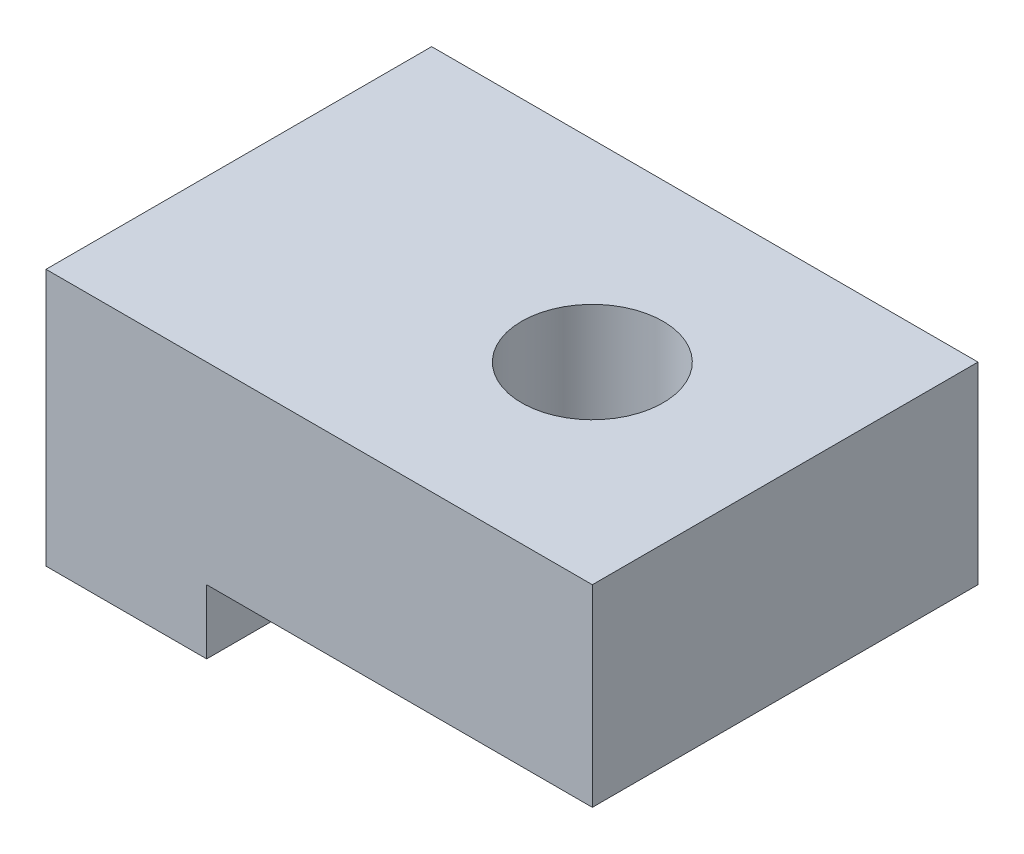
SolidWorks part; units mm, degrees
material "可锻铸铁"
ref_plane "前视基准面" through (0, 0, 0) normal (0, 0, 1) x (1, 0, 0)
ref_plane "上视基准面" through (0, 0, 0) normal (0, 1, 0) x (1, 0, 0)
ref_plane "右视基准面" through (0, 0, 0) normal (1, 0, 0) x (0, 0, -1)
sketch "草图1" plane through (0, 0, 0) normal (0, 0, 1) x (1, 0, 0)
  line L1 (0, 0) -> (-85, 0)
  line L2 (0, 0) -> (0, -40)
  line L3 (0, -40) -> (-85, -40)
  line L4 (-85, 0) -> (-85, -40)
  dimension "D1" = 40
  dimension "D2" = 85
extrude "凸台-拉伸1" add sketch "草图1" along normal mid plane 60
sketch "草图2" plane through (0, 0, 30) normal (0, 0, 1) x (1, 0, 0)
  line L1 (-60, -40) -> (0, -40)
  line L2 (-60, -40) -> (-60, -30)
  line L3 (-60, -30) -> (0, -30)
  line L4 (0, -40) -> (0, -30)
  line L5 (0, 0) -> (-85, 0) construction
  line L6 (-85, 0) -> (-85, -40) construction
  dimension "D1" = 25
  dimension "D2" = 30
extrude "切除-拉伸2" cut sketch "草图2" against normal through all
sketch "草图3" plane through (0, 0, 0) normal (0, 1, 0) x (1, 0, 0)
  line L0 (0, -30) -> (0, 30) construction
  circle A0 centre (-30, 0) radius 11
  dimension "D1" = 22
  dimension "D2" = 30
extrude "切除-拉伸3" cut sketch "草图3" against normal through all
